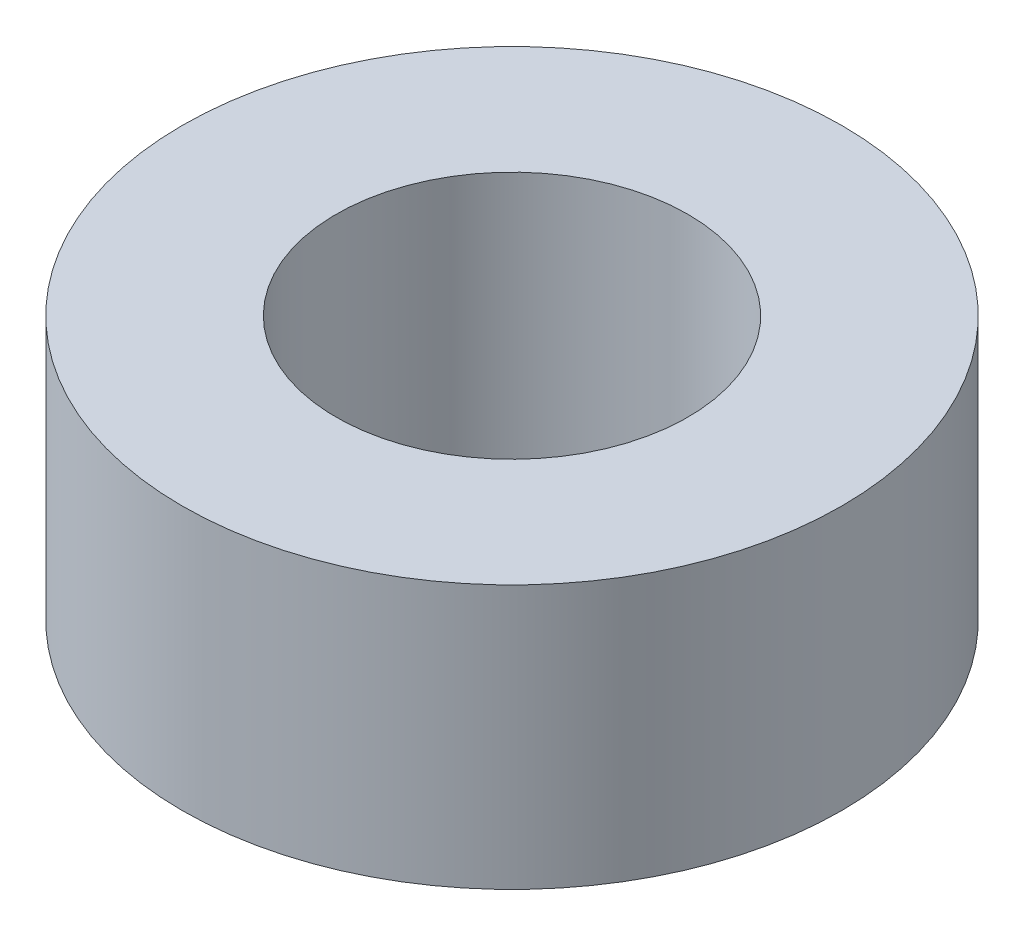
SolidWorks part; units mm, degrees
ref_plane "Front Plane" through (0, 0, 0) normal (0, 0, 1) x (1, 0, 0)
ref_plane "Top Plane" through (0, 0, 0) normal (0, 1, 0) x (1, 0, 0)
ref_plane "Right Plane" through (0, 0, 0) normal (1, 0, 0) x (0, 0, -1)
sketch "Sketch1" plane through (0, 0, 0) normal (0, 1, 0) x (1, 0, 0)
  circle A0 centre (0, 0) radius 11.9062
  circle A1 centre (0, 0) radius 6.35
  dimension "D1" = 12.7
  dimension "D2" = 23.8125
extrude "Boss-Extrude1" add sketch "Sketch1" along normal blind 9.525
